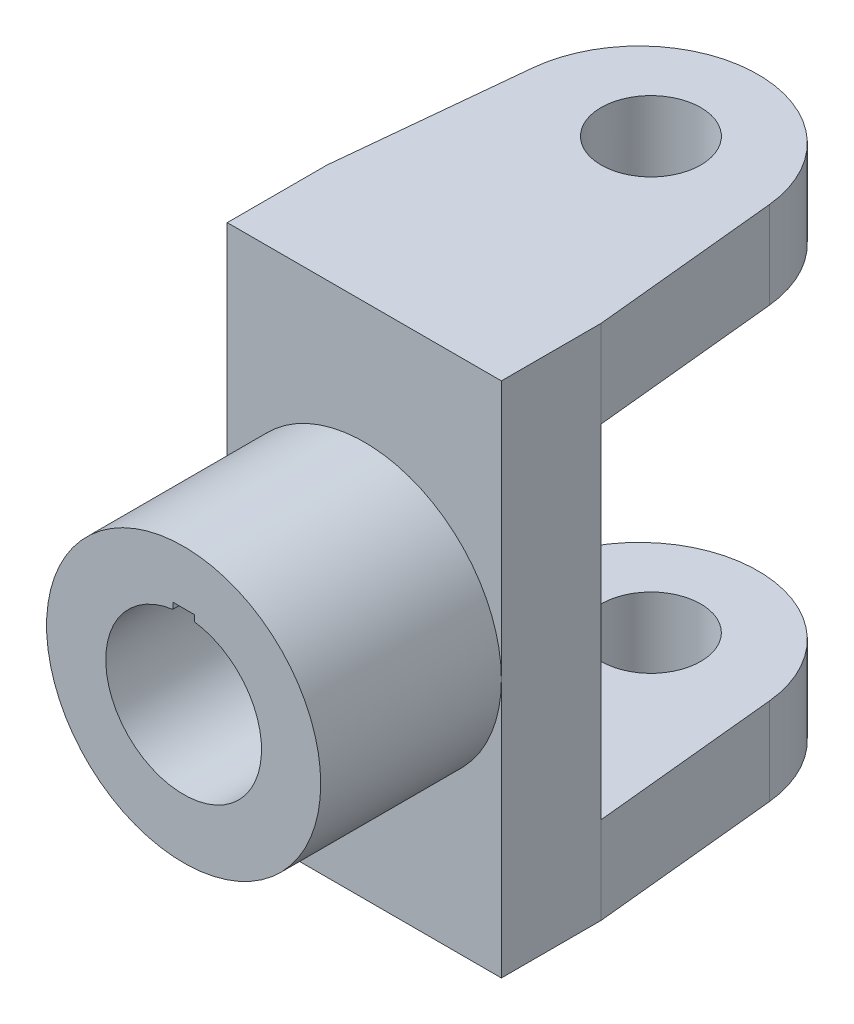
SolidWorks part; units mm, degrees
ref_plane "Front Plane" through (0, 0, 0) normal (0, 0, 1) x (1, 0, 0)
ref_plane "Top Plane" through (0, 0, 0) normal (0, 1, 0) x (1, 0, 0)
ref_plane "Right Plane" through (0, 0, 0) normal (1, 0, 0) x (0, 0, -1)
sketch "Sketch2" plane through (0, 0, 0) normal (0, 1, 0) x (1, 0, 0)
  line L0 (0, 0) -> (88, 0)
  line L4 (88, 32) -> (88, 0)
  line L5 (0, 0) -> (0, 32)
  line L7 (0, 32) -> (88, 32)
  line L8 (0, 32) -> (6, 92)
  line L9 (88, 32) -> (82, 92)
  circle A1 centre (44, 92) radius 16
  arc A3 (6, 92) -> (82, 92) centre (44, 88.2) cw
extrude "Boss-Extrude2" add sketch "Sketch2" along normal blind 166 contours L7 L5 L0 L4 | A3 L8 L7 L9 A1
sketch "Sketch5" plane through (0, 0, 0) normal (1, 0, 0) x (0, 0, -1)
  line L0 (126.3895, 28) -> (126.3895, 138)
  line L2 (32, 166) -> (32, 0) construction
  line L3 (32, 138) -> (126.3895, 138)
  line L4 (126.3895, 0) -> (126.3895, 166) construction
  line L6 (32, 28) -> (126.3895, 28)
  line L7 (32, 138) -> (32, 28)
extrude "Cut-Extrude1" cut sketch "Sketch5" along normal blind 166
sketch "Sketch6" plane through (0, 0, 0) normal (0, 0, 1) x (1, 0, 0)
  line L1 (40.5086, 107.755) -> (40.5086, 109.755)
  line L2 (40.5086, 109.755) -> (47.5086, 109.755)
  line L3 (47.5086, 109.755) -> (47.5086, 107.7526)
  arc A0 (40.5086, 107.755) -> (47.5086, 107.7526) centre (44, 83) ccw
  circle A1 centre (44, 83) radius 44
extrude "Boss-Extrude4" add sketch "Sketch6" along normal blind 58
